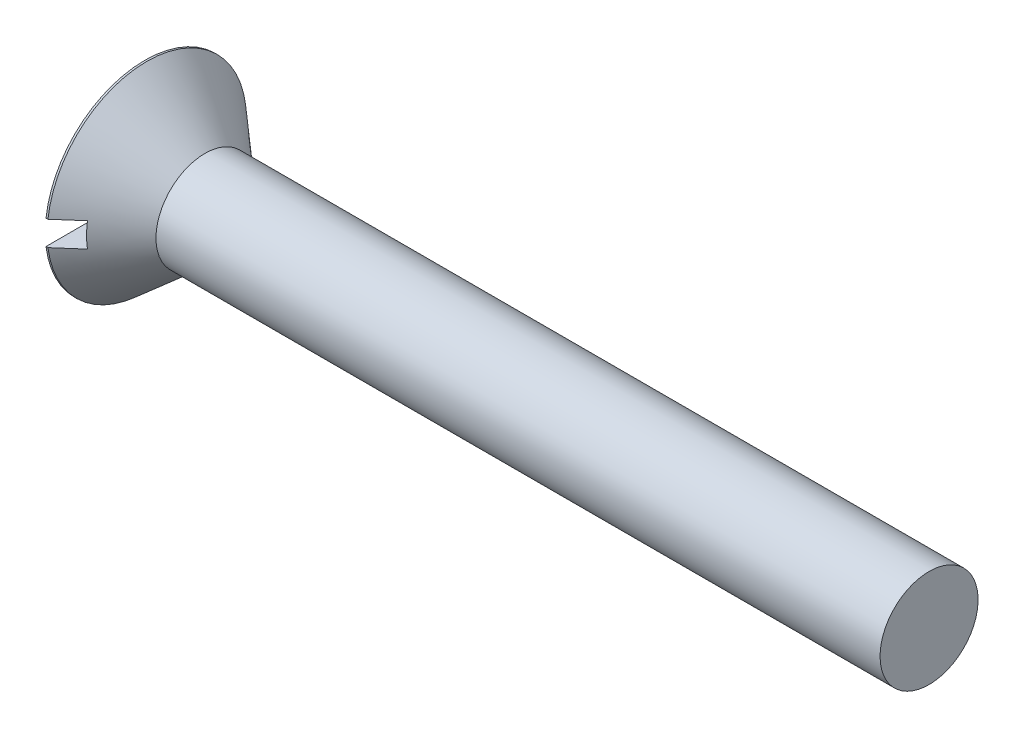
SolidWorks part; units mm, degrees
revolve "Base-Revolve" add sketch "BodySke" angle 360 about L5
sketch "BodySke" plane through (0, 0, 0) normal (0, 0, 1) x (1, 0, 0)
  line L0 (0, 0) -> (0, 9.6774)
  line L1 (0, 9.6774) -> (0.1881, 9.6774)
  line L2 (5.842, 4.7625) -> (76.2, 4.7625)
  line L3 (76.2, 4.7625) -> (76.2, 0)
  line L4 (76.2, 0) -> (0, 0)
  line L5 (-6.35, 0) -> (82.55, 0) construction
  line L6 (5.842, -4.7625) -> (76.2, -4.7625) construction
  line L7 (0.1881, -9.6774) -> (5.842, -4.7625) construction
  line L8 (0.1881, 9.6774) -> (5.842, 4.7625)
  line L9 (0, -9.6774) -> (0.1881, -9.6774) construction
  line L10 (7.4295, 6.35) -> (7.4295, -3.175) construction
  line L11 (44.45, 6.35) -> (44.45, -3.175) construction
  dimension "Diameter" = 9.525
  dimension "Length" = 76.2
  dimension "Head_ht" = 5.842
  dimension "Head_dia" = 19.3548
  dimension "Head_ang" = 82
  dimension "D6" = 0.1881
  dimension "Advance" = 1.5875
  dimension "Thread_nom" = 31.75
cosmetic thread "ThreadCosmetic" [suppressed] parameters "Thread_length"=31.75, "Thread_minor"=7.9248
extrude "Slot" cut sketch "Sketch6" against normal blind 2.2352
sketch "Sketch6" plane through (0, 0, 0) normal (-1, 0, 0) x (0, 0, 1)
  line L0 (-9.6774, -1.1938) -> (9.6774, -1.1938)
  line L1 (-9.6774, -1.1938) -> (-9.6774, 1.1938)
  line L2 (9.6774, 1.1938) -> (-9.6774, 1.1938)
  line L3 (9.6774, 1.1938) -> (9.6774, -1.1938)
  dimension "Slot_width" = 2.3876
  dimension "D1" = 1.1938
  dimension "D2" = 19.3548
  dimension "D3" = 9.6774
ref_plane "Plane1" through (0, 0, 0) normal (0, 0, 1) x (1, 0, 0)
ref_plane "Plane2" through (0, 0, 0) normal (0, 1, 0) x (1, 0, 0)
ref_plane "Plane3" through (0, 0, 0) normal (1, 0, 0) x (0, 0, -1)
sketch "ThdSchSke" plane through (0, 0, 0) normal (0, 0, 1) x (1, 0, 0)
  line L0 (44.45, -3.9624) -> (43.8898, -4.7625)
  line L1 (44.45, -3.9624) -> (45.0103, -4.7625)
  line L2 (45.0103, -4.7625) -> (45.0103, -5.9531)
  line L3 (-3.175, 0) -> (5.1513, 0) construction
  line L5 (45.0103, -5.9531) -> (43.8898, -5.9531)
  line L6 (43.8898, -5.9531) -> (43.8898, -4.7625)
  line L7 (0, 9.6774) -> (0, 1.1938) construction
  dimension "Diameter" = 9.525
  dimension "Thread_minor" = 7.9248
  dimension "Start" = 44.45
revolve "ThreadSchematic" [suppressed] cut sketch "ThdSchSke" angle 360 about L3
pattern_linear "ThdSchPat" [suppressed]
equation "\"D1@Sketch6\" = \"Slot_width@Sketch6\" / 2"
equation "\"D2@Sketch6\" = \"Head_dia@BodySke\""
equation "\"D3@Sketch6\" = \"D2@Sketch6\" / 2"
equation "\"Thread_length@ThreadCosmetic\" = ((sgn( (\"Length@BodySke\" - \"Advance@BodySke\" - \"Head_ht@BodySke\" ) - \"Thread_nom@BodySke\" )-1)*( (\"Length@BodySke\" - \"Advance@BodySke\" - \"Head_ht@BodySke\" ) - \"Thread_nom@BodySke\" ))/-2+ \"Thread_nom@BodySke\""
equation "\"Thread_minor@ThdSchSke\" = \"Thread_minor@ThreadCosmetic\""
equation "\"Diameter@ThdSchSke\" = \"Diameter@BodySke\""
equation "\"Overcut@ThdSchSke\" = \"Diameter@BodySke\" * 1.25"
equation "\"Start@ThdSchSke\" = 0.000001 + \"Length@BodySke\" - \"Thread_length@ThreadCosmetic\"  '---Countersunk---"
equation "\"Num_threads@ThdSchPat\" = int( \"Thread_length@ThreadCosmetic\" / \"Advance@BodySke\" + 0.999 )  + 1"
equation "\"Advance@ThdSchPat\" = \"Thread_length@ThreadCosmetic\" /  (\"Num_threads@ThdSchPat\" - 1) 'relax it"
